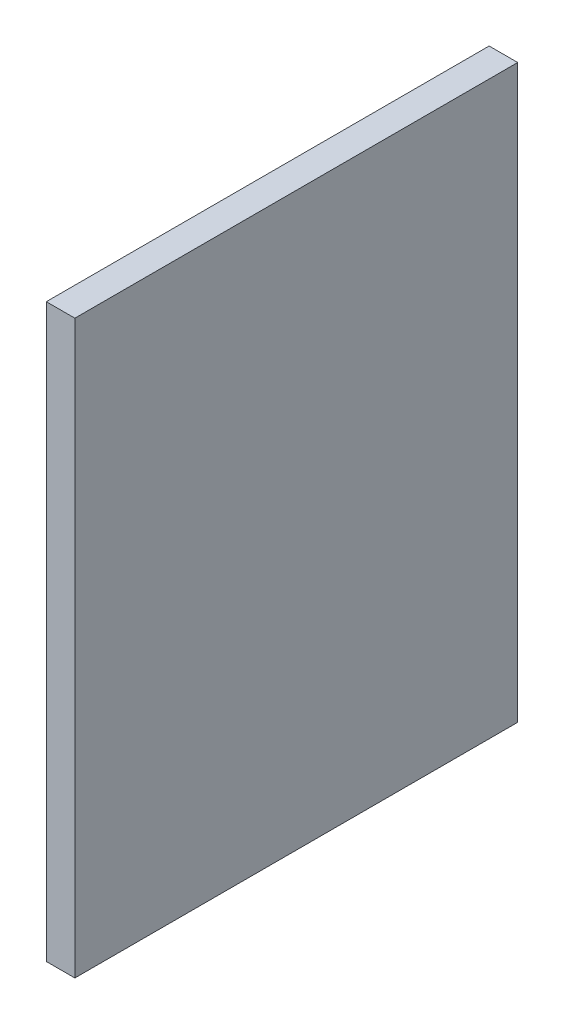
SolidWorks part; units mm, degrees
ref_plane "Alzado" through (0, 0, 0) normal (0, 0, 1) x (1, 0, 0)
ref_plane "Planta" through (0, 0, 0) normal (0, 1, 0) x (1, 0, 0)
ref_plane "Vista lateral" through (0, 0, 0) normal (1, 0, 0) x (0, 0, -1)
ref_plane "Plano_CajaSujetadoraOeste" through (0, 630, 0) normal (0, 1, 0) x (1, 0, 0)
sketch "SkCajaSujetadoraOeste" plane through (0, 630, 0) normal (0, 1, 0) x (1, 0, 0)
  line L1 (-155, -155) -> (-135, -155)
  line L2 (-155, -155) -> (-155, 155)
  line L3 (-155, 155) -> (-135, 155)
  line L4 (-135, -155) -> (-135, 155)
extrude "CajaSujetadoraOeste" add sketch "SkCajaSujetadoraOeste" along normal blind 400 separate body
